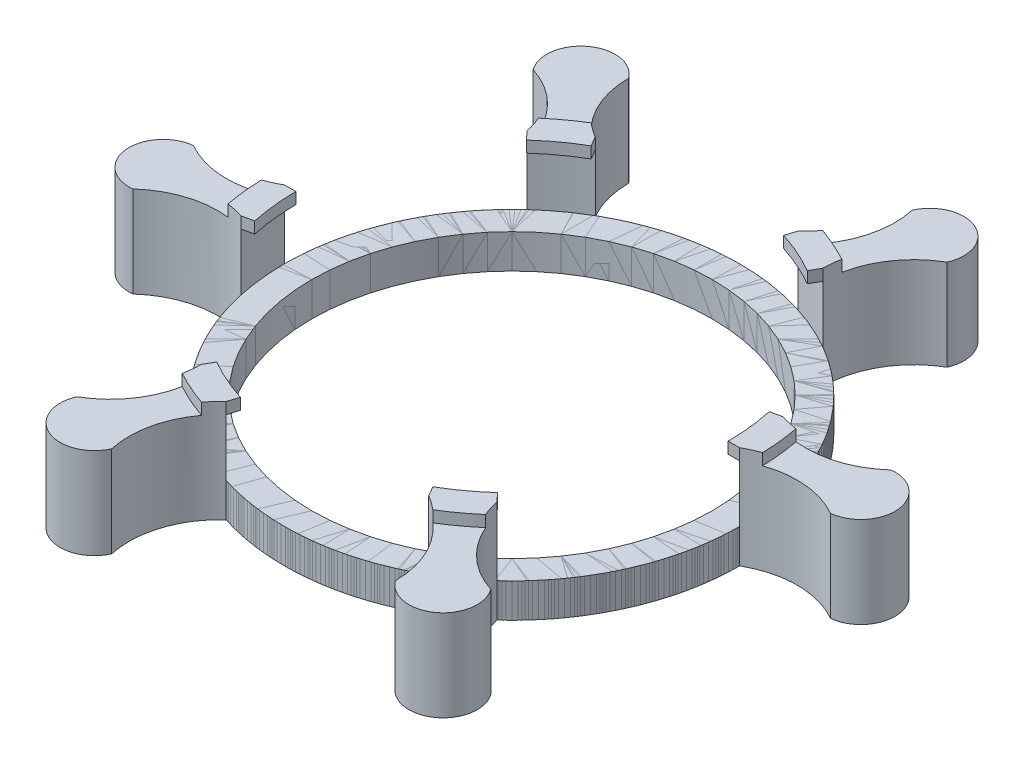
SolidWorks part; units mm, degrees
ref_plane "Front Plane" through (0, 0, 0) normal (0, 0, 1) x (1, 0, 0)
ref_plane "Top Plane" through (0, 0, 0) normal (0, 1, 0) x (1, 0, 0)
ref_plane "Right Plane" through (0, 0, 0) normal (1, 0, 0) x (0, 0, -1)
sketch "Sketch1" plane through (0, 0, 0) normal (0, 1, 0) x (1, 0, 0)
  circle A0 centre (0, 0) radius 63.5
  circle A1 centre (0, 0) radius 55.88
extrude "Boss-Extrude1" add sketch "Sketch1" along normal blind 9.525
sketch "Sketch2" plane through (0, 9.525, 0) normal (0, 1, 0) x (1, 0, 0)
  arc A0 (62.0421, 13.5288) -> (86.8589, 18.9403) centre (69.764, 37.7266) ccw
  arc A1 (63.5, 0) -> (88.9, 0) centre (76.2, -21.997) cw
  circle A2 centre (0, 0) radius 63.5 construction
  arc A4 (88.9, 0) -> (86.8589, 18.9403) centre (87.8795, 9.4702) ccw
  arc A5 (63.5, 0) -> (62.0421, 13.5288) centre (0, 0) ccw
extrude "Boss-Extrude2" add sketch "Sketch2" against normal blind 9.525 and the other way blind 15.875
sketch "Sketch3" plane through (0, 25.4, 0) normal (0, 1, 0) x (1, 0, 0)
  line L0 (60.325, 0) -> (63.5, 0)
  line L1 (58.94, 12.8524) -> (62.0421, 13.5288)
  arc A0 (67.9151, 2.0138) -> (66.7849, 12.5019) centre (0, 0) ccw
  arc A1 (60.325, 0) -> (58.94, 12.8524) centre (0, 0) ccw
  arc A2 (63.5, 0) -> (67.9151, 2.0138) centre (76.2, -21.997) cw
  arc A3 (62.0421, 13.5288) -> (66.7849, 12.5019) centre (69.764, 37.7266) ccw
  arc A4 (62.0421, 13.5288) -> (86.8589, 18.9403) centre (69.764, 37.7266) ccw construction
  arc A5 (63.5, 0) -> (62.0421, 13.5288) centre (0, 0) ccw construction
extrude "Boss-Extrude3" add sketch "Sketch3" along normal blind 3.175
pattern_circular "CirPattern1" count 6 over 360 about axis through (0, 0, 0) along (0, 1, 0) of bodies 103
sketch "Sketch4" plane through (0, 25.4, 0) normal (0, 1, 0) x (1, 0, 0)
  line L0 (0, 0) -> (84.6386, -49.2272)
  line L1 (84.6386, -49.2272) -> (90.2983, -37.858)
  line L2 (90.2983, -37.858) -> (0, 0)
  line L3 (97.3496, 10.4907) -> (57.76, -79.0619)
  arc A0 (62.0421, 13.5288) -> (86.8589, 18.9403) centre (69.764, 37.7266) ccw
  arc A1 (86.8589, 18.9403) -> (97.3496, 10.4907) centre (87.8795, 9.4702) cw
  arc A2 (88.9, 0) -> (86.8589, 18.9403) centre (87.8795, 9.4702) ccw construction
  circle A3 centre (0, 0) radius 97.9133
  arc A4 (44.45, -76.9897) -> (59.8323, -65.7519) centre (52.1411, -71.3708) ccw construction
